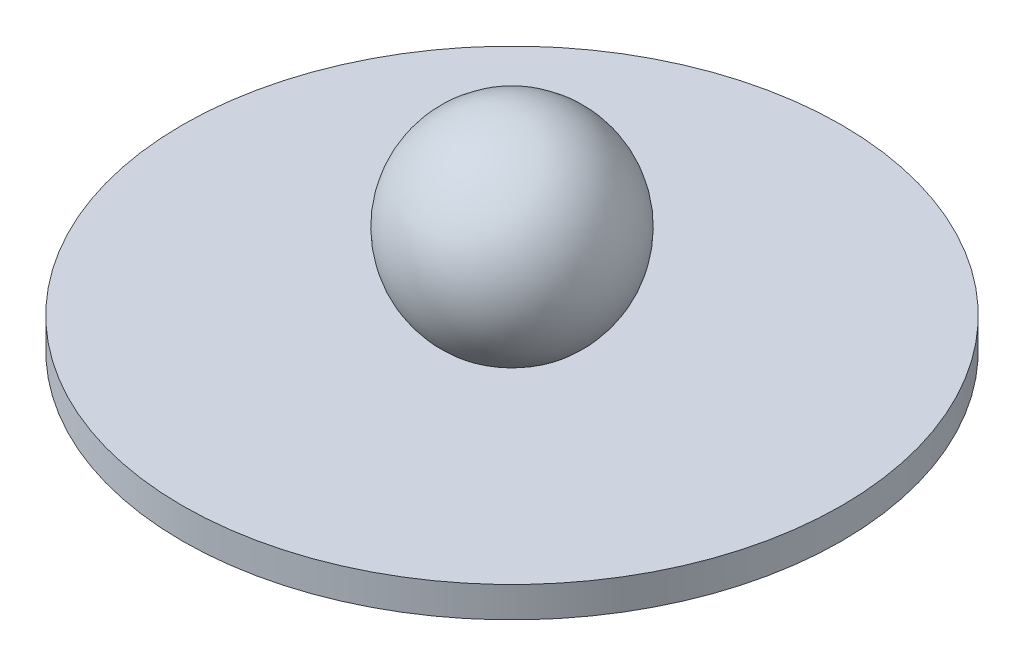
SolidWorks part; units mm, degrees
ref_plane "Front" through (0, 0, 0) normal (0, 0, 1) x (1, 0, 0)
ref_plane "Top" through (0, 0, 0) normal (0, 1, 0) x (1, 0, 0)
ref_plane "Right" through (0, 0, 0) normal (1, 0, 0) x (0, 0, -1)
sketch "Sketch1" plane through (0, 0, 0) normal (0, 0, 1) x (1, 0, 0)
  line L0 (0, 0) -> (0, 90.5826) construction
  line L1 (62.865, 12.7) -> (62.865, 6.858)
  line L2 (62.865, 6.858) -> (57.785, 6.858)
  line L3 (57.785, 6.858) -> (50.927, 0)
  line L4 (50.927, 0) -> (0, 0)
  line L5 (0, 0) -> (0, 12.7)
  line L6 (0, 12.7) -> (62.865, 12.7)
  dimension "D1" = 62.865
  dimension "D2" = 12.7
  dimension "D3" = 45
  dimension "D4" = 5.842
  dimension "D5" = 5.08
revolve "Revolve1" add sketch "Sketch1" angle 360 about L0
sketch "Sketch2" plane through (0, 0, 0) normal (0, 0, 1) x (1, 0, 0)
  line L0 (0, 0) -> (0, 27.2643) construction
  line L1 (0, 46.3143) -> (0, 8.2143)
  arc A0 (0, 8.2143) -> (0, 46.3143) centre (0, 27.2643) ccw
  dimension "D1" = 38.1
revolve "Revolve2" add sketch "Sketch2" angle 360 about L0
